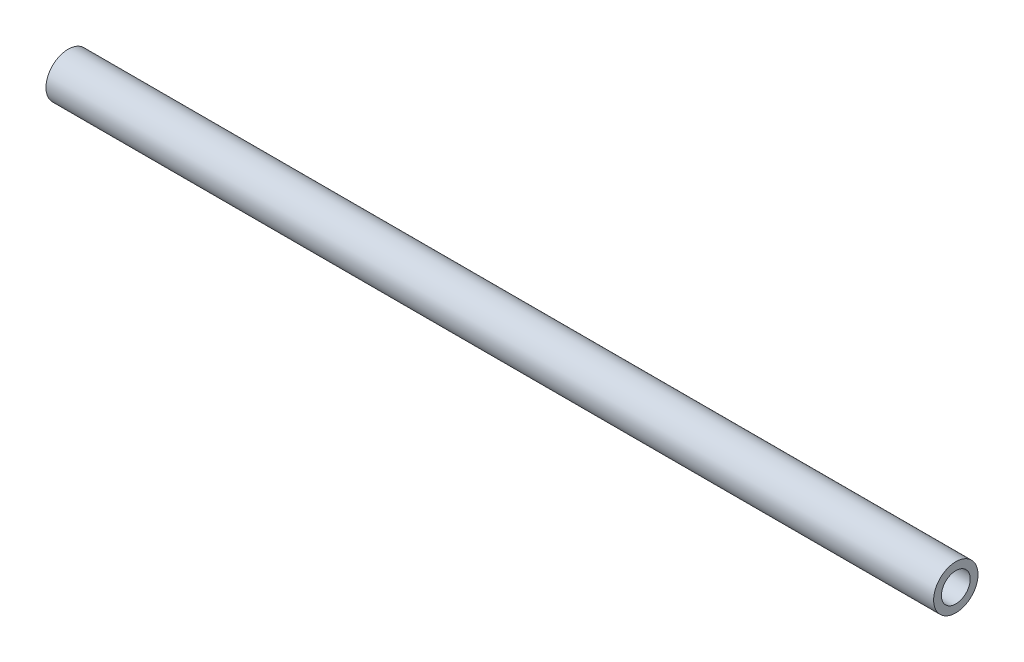
SolidWorks part; units mm, degrees
ref_plane "Спереди" through (0, 0, 0) normal (0, 0, 1) x (1, 0, 0)
ref_plane "Сверху" through (0, 0, 0) normal (0, 1, 0) x (1, 0, 0)
ref_plane "Справа" through (0, 0, 0) normal (1, 0, 0) x (0, 0, -1)
other "Configuration Table"
sketch "Эскиз1" plane through (0, 0, 0) normal (1, 0, 0) x (0, 0, -1)
  circle A0 centre (0, 0) radius 6.5
  circle A1 centre (0, 0) radius 10
  dimension "D1" = 13
  dimension "D2" = 20
extrude "Бобышка-Вытянуть1" add sketch "Эскиз1" along normal blind 400
